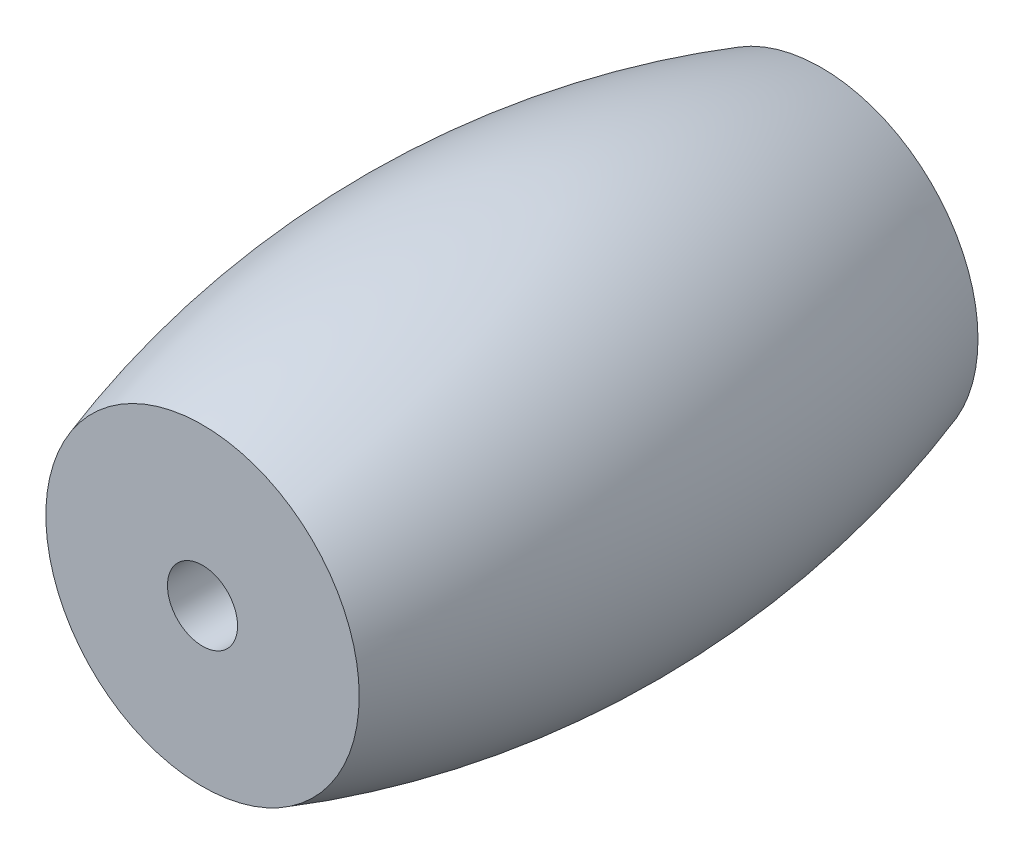
SolidWorks part; units mm, degrees
ref_plane "Ebene vorne" through (0, 0, 0) normal (0, 0, 1) x (1, 0, 0)
ref_plane "Ebene oben" through (0, 0, 0) normal (0, 1, 0) x (1, 0, 0)
ref_plane "Ebene rechts" through (0, 0, 0) normal (1, 0, 0) x (0, 0, -1)
sketch "Skizze1" plane through (0, 0, 0) normal (1, 0, 0) x (0, 0, -1)
  line L0 (-31.773, 0) -> (28.8618, 0)
  line L1 (-15, 16.7) -> (15, 16.7)
  line L2 (-15, 16.7) -> (-15, 1.7)
  line L3 (-15, 1.7) -> (15, 1.7)
  line L4 (15, 16.7) -> (15, 1.7)
  circle A0 centre (0, -38) radius 48
  dimension "D1" = 30
  dimension "D5" = 96
  dimension "D2" = 15
  dimension "D3" = 1.7
  dimension "D4" = 38
ref_axis "Achse1" through (0, 0, 31.773) along (0, 0, -1)
revolve "Rotation3" add sketch "Skizze1" angle 360 about axis through (0, 0, 31.773) along (0, 0, -1)
